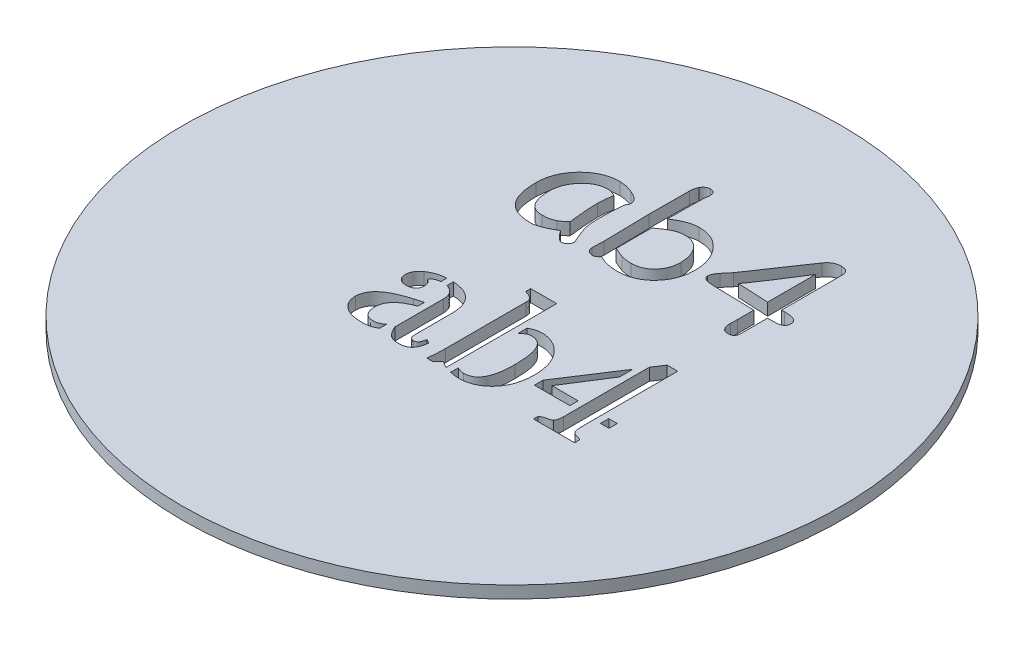
SolidWorks part; units mm, degrees
ref_plane "Front" through (0, 0, 0) normal (0, 0, 1) x (1, 0, 0)
ref_plane "Top" through (0, 0, 0) normal (0, 1, 0) x (1, 0, 0)
ref_plane "Right" through (0, 0, 0) normal (1, 0, 0) x (0, 0, -1)
sketch "Эскиз1" plane through (0, 0, 0) normal (0, 1, 0) x (1, 0, 0)
  text T0 "ab4" font "Comic Sans MS" height 6.35
  text T1 "ab4" font "Stardos Stencil" height 6.35
  point P5 (0, 0)
sketch "Эскиз2" plane through (0, 0, 0) normal (0, 1, 0) x (1, 0, 0)
  circle A0 centre (0, 0) radius 18.8456
extrude "Бобышка-Вытянуть2" add sketch "Эскиз2" along normal blind 0.7
extrude "Вырез-Вытянуть1" cut sketch "Эскиз1" along normal blind 2.4
